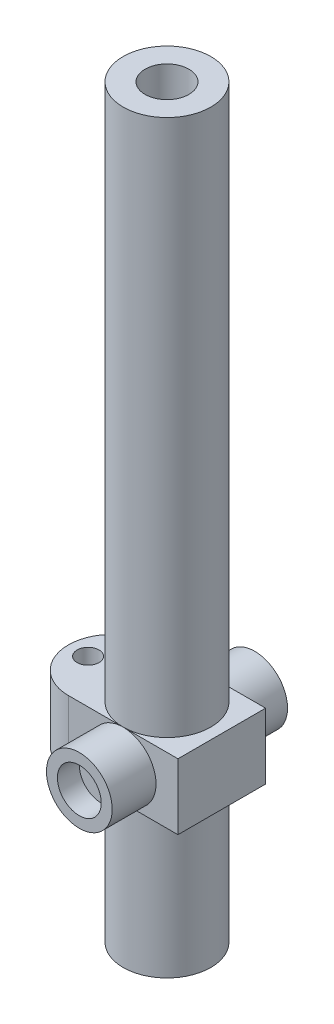
SolidWorks part; units mm, degrees
ref_plane "Front Plane" through (0, 0, 0) normal (0, 0, 1) x (1, 0, 0)
ref_plane "Top Plane" through (0, 0, 0) normal (0, 1, 0) x (1, 0, 0)
ref_plane "Right Plane" through (0, 0, 0) normal (1, 0, 0) x (0, 0, -1)
sketch "Sketch1" plane through (0, 0, 0) normal (0, 1, 0) x (1, 0, 0)
  circle A0 centre (0, 0) radius 10
  dimension "D1" = 20
extrude "Boss-Extrude1" add sketch "Sketch1" along normal blind 170
sketch "Sketch2" plane through (0, 0, 0) normal (0, 0, 1) x (1, 0, 0)
  line L0 (10, 0) -> (10, 170) construction
  line L1 (-12.5, 47.5) -> (12.5, 47.5)
  line L2 (-12.5, 47.5) -> (-12.5, 32.5)
  line L3 (-12.5, 32.5) -> (12.5, 32.5)
  line L4 (12.5, 47.5) -> (12.5, 32.5)
  line L5 (-12.5, 47.5) -> (12.5, 32.5) construction
  line L6 (-12.5, 32.5) -> (12.5, 47.5) construction
  line L7 (-10, 0) -> (10, 0) construction
  point P0 (0, 40)
  dimension "D1" = 25
  dimension "D2" = 15
  dimension "D3" = 10
  dimension "D4" = 40
extrude "Boss-Extrude3" add sketch "Sketch2" along normal mid plane 20
sketch "Sketch3" plane through (0, 0, 10) normal (0, 0, 1) x (1, 0, 0)
  circle A0 centre (0, 40) radius 7.5
  dimension "D1" = 15
extrude "Boss-Extrude4" add sketch "Sketch3" along normal mid plane 40 from offset 10 offset against normal yes
sketch "Sketch4" plane through (0, 170, 0) normal (0, 1, 0) x (1, 0, 0)
  circle A0 centre (0, 0) radius 5
  dimension "D1" = 10
extrude "Cut-Extrude1" cut sketch "Sketch4" against normal blind 80
sketch "Sketch5" plane through (0, 0, -20) normal (0, 0, -1) x (-1, 0, 0)
  circle A0 centre (0, 40) radius 5
  dimension "D1" = 10
extrude "Cut-Extrude2" cut sketch "Sketch5" against normal blind 5
mirror "Mirror1" about plane through (0, 0, 0) normal (0, 0, 1) of "Cut-Extrude2"
sketch "Sketch6" plane through (0, 32.5, 0) normal (0, -1, 0) x (1, 0, 0)
  line L0 (-12.5, 10) -> (-12.5, -10) construction
  line L1 (-12.5, 10) -> (-12.5, -10)
  arc A0 (-12.5, 10) -> (-12.5, -10) centre (-12.5, 0) ccw
extrude "Boss-Extrude5" add sketch "Sketch6" against normal blind 15
sketch "Sketch7" plane through (0, 32.5, 0) normal (0, -1, 0) x (1, 0, 0)
  circle A0 centre (-18, 0) radius 2.5
  dimension "D1" = 5
  dimension "D2" = 18
extrude "Cut-Extrude3" cut sketch "Sketch7" against normal blind 15
